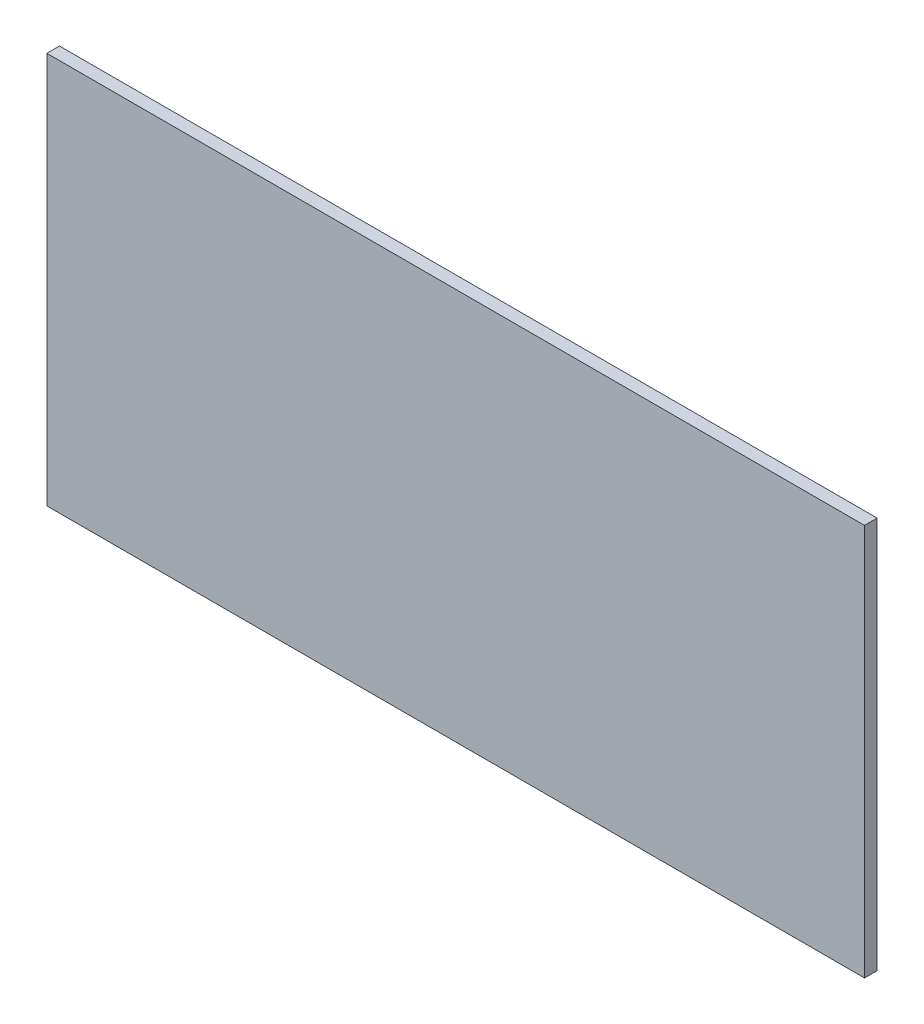
SolidWorks part; units mm, degrees
ref_plane "Front Plane" through (0, 0, 0) normal (0, 0, 1) x (1, 0, 0)
ref_plane "Top Plane" through (0, 0, 0) normal (0, 1, 0) x (1, 0, 0)
ref_plane "Right Plane" through (0, 0, 0) normal (1, 0, 0) x (0, 0, -1)
sketch "Sketch1" plane through (0, 0, 0) normal (0, 0, 1) x (1, 0, 0)
  line L1 (0, 0) -> (194, 0)
  line L2 (0, 0) -> (0, 93)
  line L3 (0, 93) -> (194, 93)
  line L4 (194, 0) -> (194, 93)
  dimension "D1" = 194
  dimension "D2" = 93
extrude "Profile" add sketch "Sketch1" along normal blind 3
equation "\"Profile_Depth\" = 3mm"
equation "\"D1@Profile\" = \"Profile_Depth\""
equation "\"Profile_Sketch_1\" = 194mm"
equation "\"D1@Sketch1\" = \"Profile_Sketch_1\""
equation "\"Profile_Sketch_2\" = 93mm"
equation "\"D2@Sketch1\" = \"Profile_Sketch_2\""
equation "\"EnvelopeWidth\" = 194mm"
equation "\"EnvelopeHeight\" = 93mm"
